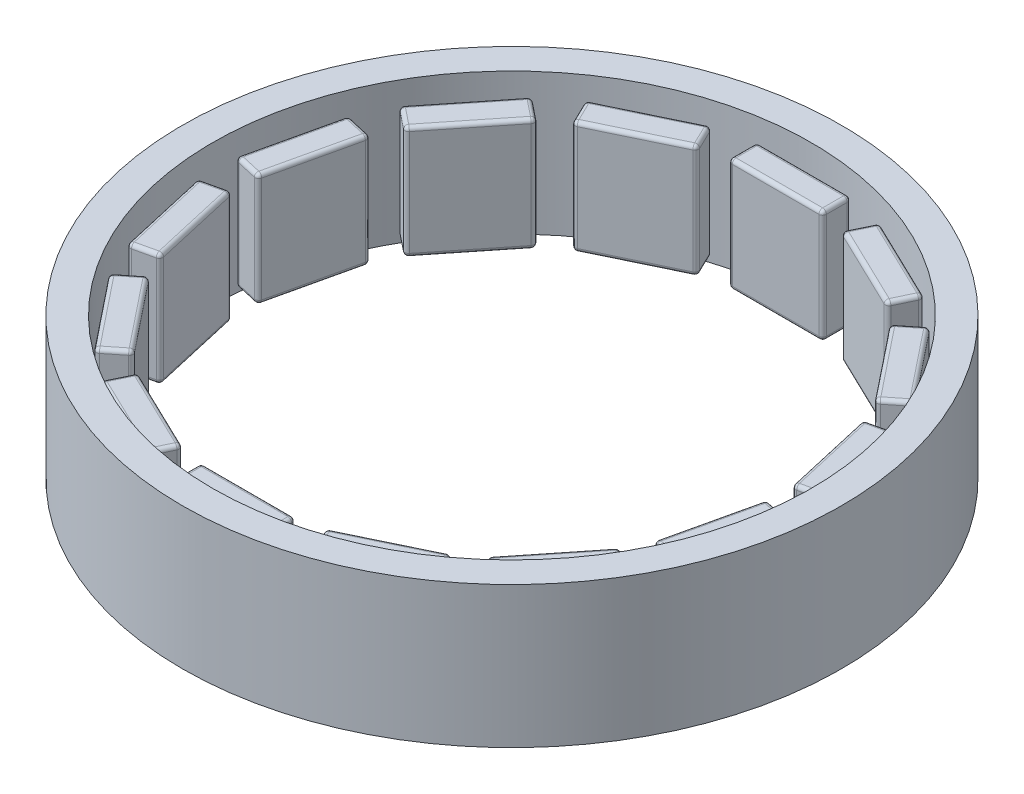
SolidWorks part; units mm, degrees
ref_plane "Спереди" through (0, 0, 0) normal (0, 0, 1) x (1, 0, 0)
ref_plane "Сверху" through (0, 0, 0) normal (0, 1, 0) x (1, 0, 0)
ref_plane "Справа" through (0, 0, 0) normal (1, 0, 0) x (0, 0, -1)
sketch "Эскиз1" plane through (0, 0, 0) normal (0, 1, 0) x (1, 0, 0)
  circle A0 centre (0, 0) radius 17.5
  circle A1 centre (0, 0) radius 15.9
  dimension "D1" = 35
  dimension "D2" = 31.8
extrude "Бобышка-Вытянуть1" add sketch "Эскиз1" along normal blind 7.5
sketch "Эскиз2" plane through (0, 7.5, 0) normal (0, 1, 0) x (1, 0, 0)
  line L1 (-2.3, 14) -> (2.3, 14)
  line L2 (-2.5, 14.2) -> (-2.5, 15.3)
  line L3 (-2.3, 15.5) -> (2.3, 15.5)
  line L4 (2.5, 14.2) -> (2.5, 15.3)
  line L5 (-2.5, 14) -> (2.5, 15.5) construction
  line L6 (-2.5, 15.5) -> (2.5, 14) construction
  arc A0 (2.3, 15.5) -> (2.5, 15.3) centre (2.3, 15.3) cw
  arc A1 (2.3, 14) -> (2.5, 14.2) centre (2.3, 14.2) ccw
  arc A2 (-2.3, 14) -> (-2.5, 14.2) centre (-2.3, 14.2) cw
  arc A3 (-2.5, 15.3) -> (-2.3, 15.5) centre (-2.3, 15.3) cw
  point P0 (0, 14.75)
  dimension "D5" = 0.2
  dimension "D1" = 5
  dimension "D2" = 1.5
  dimension "D3" = 14
  dimension "D4" = 2.5
extrude "Бобышка-Вытянуть2" add sketch "Эскиз2" against normal blind 6 from offset 1 separate body offset against normal yes
fillet "Скругление1" radius 0.2 16 edges at (0, 0.5, -15.5) (-2.4414, 0.5, -15.4414) (-2.5, 0.5, -14.75) (-2.4414, 0.5, -14.0586) (0, 0.5, -14) (2.4414, 0.5, -14.0586) (2.5, 0.5, -14.75) (2.4414, 0.5, -15.4414) (2.5, 6.5, -14.75) (2.4414, 6.5, -14.0586) (0, 6.5, -14) (-2.4414, 6.5, -14.0586) (-2.5, 6.5, -14.75) (-2.4414, 6.5, -15.4414) (0, 6.5, -15.5) (2.4414, 6.5, -15.4414)
sketch "Эскиз3" plane through (0, 0, 0) normal (1, 0, 0) x (0, 0, -1)
  line L0 (0, -2.2413) -> (0, 10.0283) construction
pattern_circular "Круговой массив3" count 14 over 360 about axis through (0, 0, 0) along (0, 1, 0) of bodies 102
